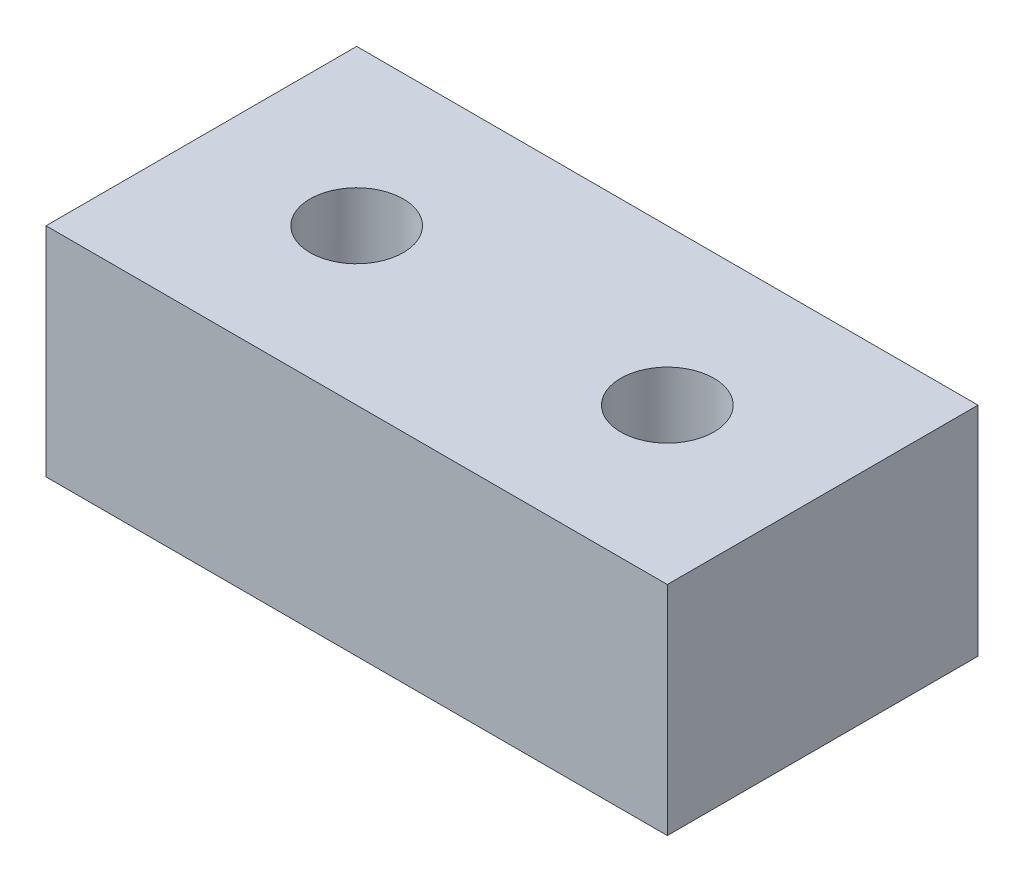
SolidWorks part; units mm, degrees
ref_plane "Front Plane" through (0, 0, 0) normal (0, 0, 1) x (1, 0, 0)
ref_plane "Top Plane" through (0, 0, 0) normal (0, 1, 0) x (1, 0, 0)
ref_plane "Right Plane" through (0, 0, 0) normal (1, 0, 0) x (0, 0, -1)
sketch "Sketch1" plane through (0, 0, 0) normal (0, 1, 0) x (1, 0, 0)
  line L1 (-10, -5) -> (10, -5)
  line L2 (-10, -5) -> (-10, 5)
  line L3 (-10, 5) -> (10, 5)
  line L4 (10, -5) -> (10, 5)
  line L5 (-10, -5) -> (10, 5) construction
  line L6 (-10, 5) -> (10, -5) construction
  point P0 (0, 0)
  dimension "D1" = 20
  dimension "D2" = 10
extrude "Boss-Extrude1" add sketch "Sketch1" along normal blind 7
sketch "Sketch2" plane through (0, 7, 0) normal (0, 1, 0) x (1, 0, 0)
  line L0 (5, 0) -> (-5, 0) construction
  line L1 (-5, 0) -> (5, 0) construction
  line L2 (0, 0) -> (0, 3.0744) construction
  circle A0 centre (-5, 0) radius 1.5
  circle A1 centre (5, 0) radius 1.5
  dimension "D2" = 3
  dimension "D1" = 5
extrude "Cut-Extrude1" cut sketch "Sketch2" against normal blind 10
